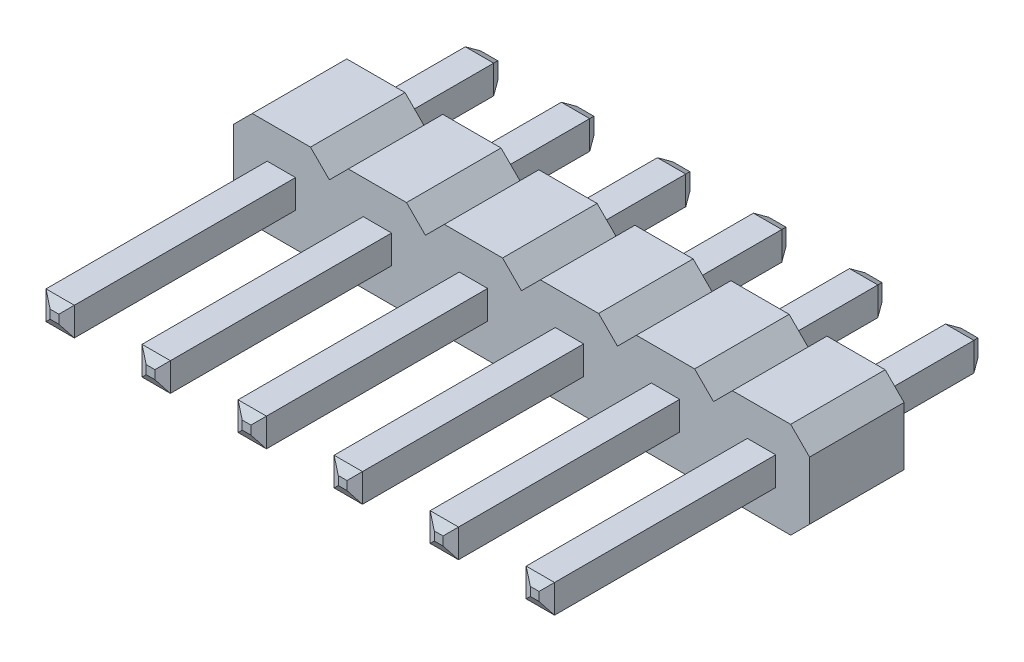
SolidWorks part; units mm, degrees
material "ABSOranžová"
ref_plane "Horní rovina" through (0, 0, 0) normal (0, 0, 1) x (1, 0, 0)
ref_plane "Přední rovina" through (0, 0, 0) normal (0, 1, 0) x (1, 0, 0)
ref_plane "Pravá rovina" through (0, 0, 0) normal (1, 0, 0) x (0, 0, -1)
sketch "Skica1" plane through (0, 0, 0) normal (0, 0, 1) x (1, 0, 0)
  line L0 (0.77, 1.27) -> (1.27, 0.77)
  line L1 (-0.77, 1.27) -> (0.77, 1.27)
  line L2 (-1.27, 0.77) -> (-1.27, -0.77)
  line L3 (-0.77, -1.27) -> (0.77, -1.27)
  line L4 (1.27, 0.77) -> (1.27, -0.77)
  line L5 (-1.27, 1.27) -> (1.27, -1.27) construction
  line L6 (-1.27, -1.27) -> (1.27, 1.27) construction
  line L7 (-0.77, 1.27) -> (-1.27, 0.77)
  line L8 (-1.27, -0.77) -> (-0.77, -1.27)
  line L9 (1.27, -0.77) -> (0.77, -1.27)
  line L10 (-2.9078, 0) -> (3.8264, 0) construction
  line L11 (-0.375, 0.375) -> (0.375, 0.375)
  line L12 (-0.375, 0.375) -> (-0.375, -0.375)
  line L13 (-0.375, -0.375) -> (0.375, -0.375)
  line L14 (0.375, 0.375) -> (0.375, -0.375)
  line L15 (-0.375, 0.375) -> (0.375, -0.375) construction
  line L16 (-0.375, -0.375) -> (0.375, 0.375) construction
  point P0 (0, 0)
  point P14 (0, 0)
  point P21 (0, 1.27)
  point P22 (0, 0)
  point P23 (0, 1.27)
  point P24 (0, 1.27)
  point P25 (0, 0.442)
  point P27 (0.0643, -0.2041)
  dimension "D1" = 2.54
  dimension "D2" = 2.54
  dimension "D3" = 0.75
extrude "Přidat vysunutím1" add sketch "Skica1" along normal blind 2.5
pattern_linear "LinPole3" count 6 spacing 2.54 along (-1, 0, 0) of "Přidat vysunutím1"
sketch "Skica2" plane through (0, 0, 2.5) normal (0, 0, 1) x (1, 0, 0)
  line L28 (-12.325, -0.375) -> (-12.325, 0.375)
  line L29 (-13.075, -0.375) -> (-12.325, -0.375)
  line L30 (-13.075, 0.375) -> (-13.075, -0.375)
  line L31 (-12.325, 0.375) -> (-13.075, 0.375)
  line L32 (-12.325, -0.375) -> (-12.325, 0.375)
  line L33 (-13.075, -0.375) -> (-12.325, -0.375)
  line L34 (-13.075, 0.375) -> (-13.075, -0.375)
  line L35 (-12.325, 0.375) -> (-13.075, 0.375)
  line L36 (-9.785, -0.375) -> (-9.785, 0.375)
  line L37 (-10.535, -0.375) -> (-9.785, -0.375)
  line L38 (-10.535, 0.375) -> (-10.535, -0.375)
  line L39 (-9.785, 0.375) -> (-10.535, 0.375)
  line L40 (-9.785, -0.375) -> (-9.785, 0.375)
  line L41 (-10.535, -0.375) -> (-9.785, -0.375)
  line L42 (-10.535, 0.375) -> (-10.535, -0.375)
  line L43 (-9.785, 0.375) -> (-10.535, 0.375)
  line L44 (-7.245, -0.375) -> (-7.245, 0.375)
  line L45 (-7.995, -0.375) -> (-7.245, -0.375)
  line L46 (-7.995, 0.375) -> (-7.995, -0.375)
  line L47 (-7.245, 0.375) -> (-7.995, 0.375)
  line L48 (-7.245, -0.375) -> (-7.245, 0.375)
  line L49 (-7.995, -0.375) -> (-7.245, -0.375)
  line L50 (-7.995, 0.375) -> (-7.995, -0.375)
  line L51 (-7.245, 0.375) -> (-7.995, 0.375)
  line L52 (-4.705, -0.375) -> (-4.705, 0.375)
  line L53 (-5.455, -0.375) -> (-4.705, -0.375)
  line L54 (-5.455, 0.375) -> (-5.455, -0.375)
  line L55 (-4.705, 0.375) -> (-5.455, 0.375)
  line L56 (-4.705, -0.375) -> (-4.705, 0.375)
  line L57 (-5.455, -0.375) -> (-4.705, -0.375)
  line L58 (-5.455, 0.375) -> (-5.455, -0.375)
  line L59 (-4.705, 0.375) -> (-5.455, 0.375)
  line L60 (-2.165, -0.375) -> (-2.165, 0.375)
  line L61 (-2.915, -0.375) -> (-2.165, -0.375)
  line L62 (-2.915, 0.375) -> (-2.915, -0.375)
  line L63 (-2.165, 0.375) -> (-2.915, 0.375)
  line L64 (-2.165, -0.375) -> (-2.165, 0.375)
  line L65 (-2.915, -0.375) -> (-2.165, -0.375)
  line L66 (-2.915, 0.375) -> (-2.915, -0.375)
  line L67 (-2.165, 0.375) -> (-2.915, 0.375)
  line L68 (0.375, -0.375) -> (0.375, 0.375)
  line L69 (-0.375, -0.375) -> (0.375, -0.375)
  line L70 (-0.375, 0.375) -> (-0.375, -0.375)
  line L71 (0.375, 0.375) -> (-0.375, 0.375)
  line L72 (0.375, -0.375) -> (0.375, 0.375)
  line L73 (-0.375, -0.375) -> (0.375, -0.375)
  line L74 (-0.375, 0.375) -> (-0.375, -0.375)
  line L75 (0.375, 0.375) -> (-0.375, 0.375)
  dimension "D1" = 0
  dimension "D2" = 0
  dimension "D3" = 0
  dimension "D4" = 0
  dimension "D5" = 0
  dimension "D6" = 0
extrude "Přidat vysunutím2" add sketch "Skica2" along normal blind 6 and the other way blind 5.5
chamfer "Zkosení2" distance 0.15 angle 60 48 edges at (-0.375, 0, -3) (0, -0.375, -3) (0.375, 0, -3) (0, 0.375, -3) (-2.915, 0, -3) (-2.54, -0.375, -3) (-2.165, 0, -3) (-2.54, 0.375, -3) (-5.455, 0, -3) (-5.08, -0.375, -3) (-4.705, 0, -3) (-5.08, 0.375, -3) (-7.995, 0, -3) (-7.62, -0.375, -3) (-7.245, 0, -3) (-7.62, 0.375, -3) (-10.535, 0, -3) (-10.16, -0.375, -3) (-9.785, 0, -3) (-10.16, 0.375, -3) (-13.075, 0, -3) (-12.7, -0.375, -3) (-12.325, 0, -3) (-12.7, 0.375, -3) (-12.325, 0, 8.5) (-12.7, -0.375, 8.5) (-13.075, 0, 8.5) (-12.7, 0.375, 8.5) (-9.785, 0, 8.5) (-10.16, -0.375, 8.5) (-10.535, 0, 8.5) (-10.16, 0.375, 8.5) (-7.245, 0, 8.5) (-7.62, -0.375, 8.5) (-7.995, 0, 8.5) (-7.62, 0.375, 8.5) (-4.705, 0, 8.5) (-5.08, -0.375, 8.5) (-5.455, 0, 8.5) (-5.08, 0.375, 8.5) (-2.165, 0, 8.5) (-2.54, -0.375, 8.5) (-2.915, 0, 8.5) (-2.54, 0.375, 8.5) (0.375, 0, 8.5) (0, -0.375, 8.5) (-0.375, 0, 8.5) (0, 0.375, 8.5)
